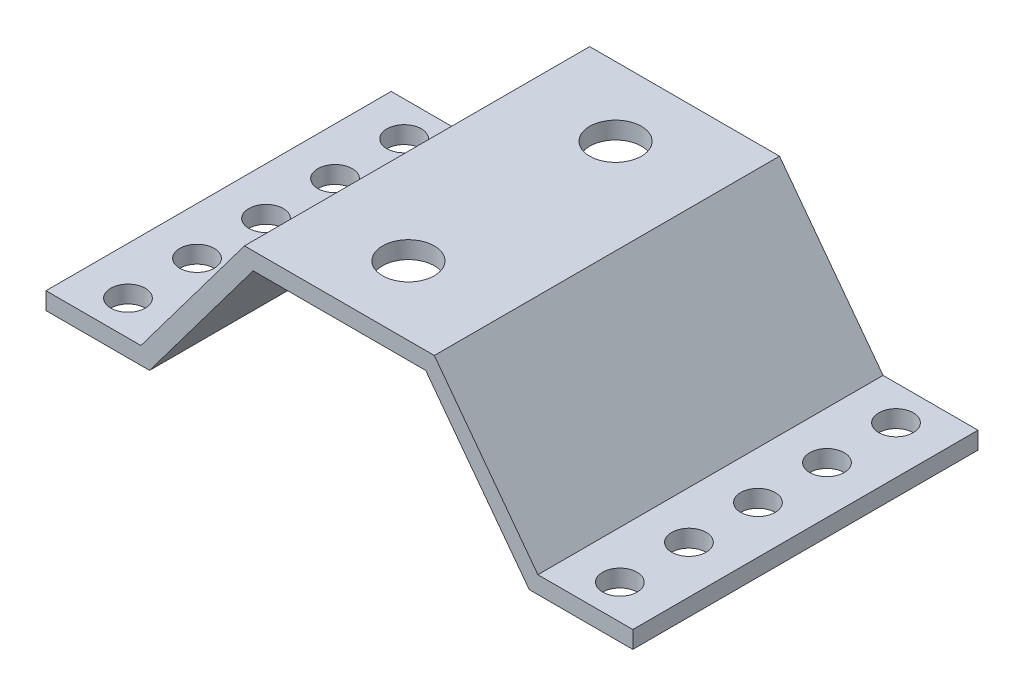
SolidWorks part; units mm, degrees
ref_plane "Front Plane" through (0, 0, 0) normal (0, 0, 1) x (1, 0, 0)
ref_plane "Top Plane" through (0, 0, 0) normal (0, 1, 0) x (1, 0, 0)
ref_plane "Right Plane" through (0, 0, 0) normal (1, 0, 0) x (0, 0, -1)
sketch "Sketch1" plane through (0, 0, 0) normal (0, 0, 1) x (1, 0, 0)
  line L0 (0, 0) -> (0, 45) construction
  line L5 (27.5, 45) -> (-27.5, 45)
  line L6 (-27.5, 45) -> (-57.5, 5)
  line L7 (-57.5, 5) -> (-85, 5)
  line L8 (-85, 5) -> (-85, 0)
  line L9 (-85, 0) -> (-55, 0)
  line L10 (-55, 0) -> (-25, 40)
  line L11 (-25, 40) -> (25, 40)
  line L12 (55, 0) -> (25, 40)
  line L13 (85, 0) -> (55, 0)
  line L14 (85, 5) -> (85, 0)
  line L15 (57.5, 5) -> (85, 5)
  line L16 (27.5, 45) -> (57.5, 5)
  point P0 (0, 0)
  point P3 (0, 0)
  point P13 (0, 40)
  dimension "D1" = 5
  dimension "D2" = 5
  dimension "D3" = 5
  dimension "D4" = 25
  dimension "D5" = 30
  dimension "D6" = 30
  dimension "D7" = 40
extrude "Boss-Extrude1" add sketch "Sketch1" along normal mid plane 100
sketch "Sketch2" plane through (0, 5, 0) normal (0, 1, 0) x (1, 0, 0)
  line L0 (-71.25, 50) -> (-71.25, -50) construction
  line L1 (-57.5, 50) -> (-85, 50) construction
  line L2 (-57.5, -50) -> (-85, -50) construction
  circle A0 centre (-71.25, -40) radius 5
  circle A1 centre (-71.25, -20) radius 5
  circle A2 centre (-71.25, 0) radius 5
  circle A3 centre (-71.25, 20) radius 5
  circle A4 centre (-71.25, 40) radius 5
  dimension "D1" = 10
  dimension "D2" = 10
  dimension "D3" = 5
extrude "Cut-Extrude1" cut sketch "Sketch2" against normal mid plane 50
mirror "Mirror1" about plane through (0, 0, 0) normal (1, 0, 0) of "Cut-Extrude1"
sketch "Sketch3" plane through (0, 45, 0) normal (0, 1, 0) x (1, 0, 0)
  line L0 (0, -50) -> (0, 50) construction
  line L1 (27.5, -50) -> (-27.5, -50) construction
  line L2 (27.5, 50) -> (-27.5, 50) construction
  line L3 (0, 0) -> (27.5, 0) construction
  line L4 (27.5, -50) -> (27.5, 50) construction
  circle A0 centre (0, -30) radius 7.5
  circle A1 centre (0, 30) radius 7.5
  dimension "D1" = 15
  dimension "D2" = 20
extrude "Cut-Extrude2" cut sketch "Sketch3" against normal mid plane 50
